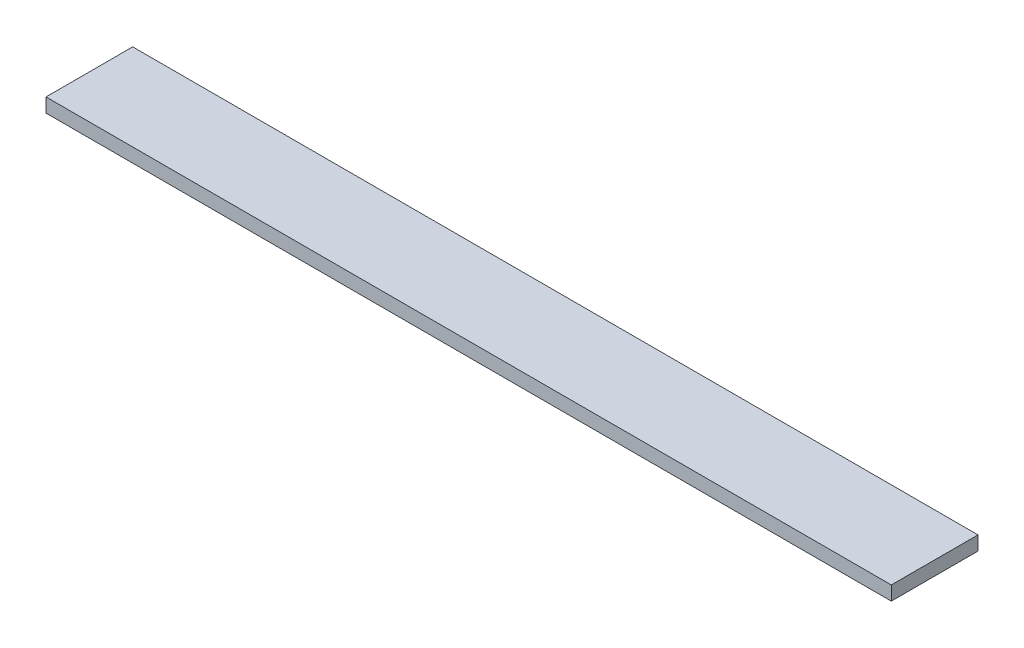
SolidWorks part; units mm, degrees
ref_plane "Front Plane" through (0, 0, 0) normal (0, 0, 1) x (1, 0, 0)
ref_plane "Top Plane" through (0, 0, 0) normal (0, 1, 0) x (1, 0, 0)
ref_plane "Right Plane" through (0, 0, 0) normal (1, 0, 0) x (0, 0, -1)
sketch "Sketch1" plane through (0, 0, 0) normal (0, 1, 0) x (1, 0, 0)
  line L1 (-654.3663, 238.6223) -> (645.7962, 238.6223)
  line L2 (-654.3663, 238.6223) -> (-654.3663, 105.2723)
  line L3 (-654.3663, 105.2723) -> (645.7962, 105.2723)
  line L4 (645.7962, 238.6223) -> (645.7962, 105.2723)
  dimension "D1" = 1300.1625
  dimension "D2" = 133.35
extrude "Boss-Extrude1" add sketch "Sketch1" along normal blind 21.59
